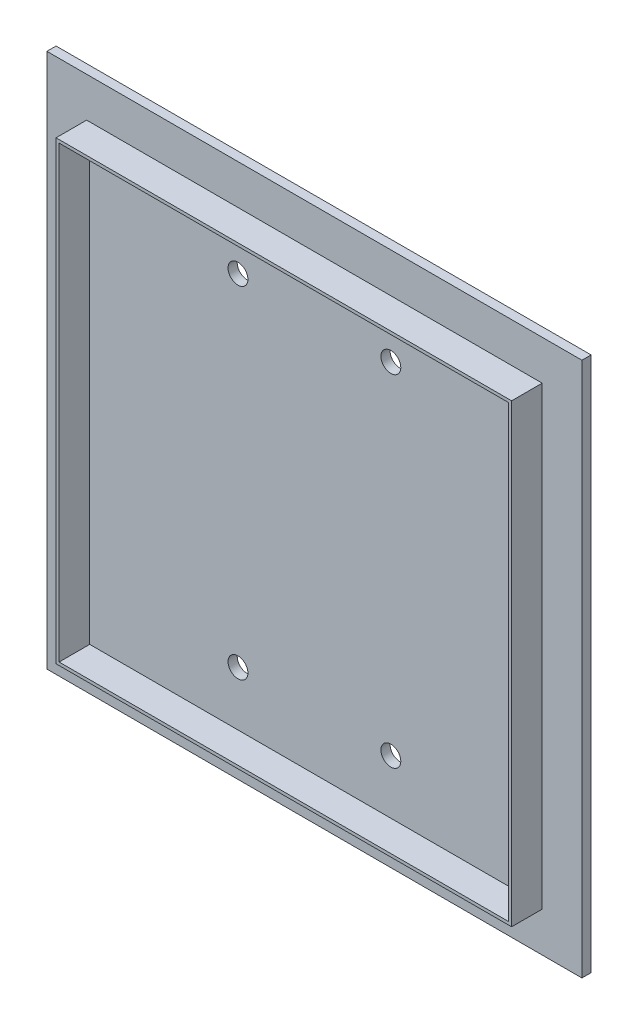
SolidWorks part; units mm, degrees
ref_plane "Plan de face" through (0, 0, 0) normal (0, 0, 1) x (1, 0, 0)
ref_plane "Plan de dessus" through (0, 0, 0) normal (0, 1, 0) x (1, 0, 0)
ref_plane "Plan de droite" through (0, 0, 0) normal (1, 0, 0) x (0, 0, -1)
sketch "Esquisse1" plane through (0, 0, 0) normal (0, 0, 1) x (1, 0, 0)
  line L1 (-175, -175) -> (175, -175)
  line L2 (-175, -175) -> (-175, 175)
  line L3 (-175, 175) -> (175, 175)
  line L4 (175, -175) -> (175, 175)
  line L5 (-175, -175) -> (175, 175) construction
  line L6 (-175, 175) -> (175, -175) construction
  point P0 (0, 0)
  dimension "D1" = 350
  dimension "D2" = 350
extrude "Boss.-Extru.1" add sketch "Esquisse1" along normal blind 26
sketch "Esquisse2" plane through (0, 0, 26) normal (0, 0, 1) x (1, 0, 0)
  line L1 (-149, 149) -> (149, 149)
  line L2 (-149, 149) -> (-149, -149)
  line L3 (-149, -149) -> (149, -149)
  line L4 (149, 149) -> (149, -149)
  line L5 (-149, 149) -> (149, -149) construction
  line L6 (-149, -149) -> (149, 149) construction
  line L7 (-175, 175) -> (175, 175)
  line L8 (-175, 175) -> (-175, -175)
  line L9 (-175, -175) -> (175, -175)
  line L10 (175, 175) -> (175, -175)
  line L11 (-175, 175) -> (175, -175) construction
  line L12 (-175, -175) -> (175, 175) construction
  point P0 (0, 0)
  point P6 (0, 0)
  dimension "D1" = 298
  dimension "D2" = 298
  dimension "D3" = 350
  dimension "350" = 350
extrude "Enlèv. mat.-Extru.1" cut sketch "Esquisse2" against normal blind 20
sketch "Esquisse3" plane through (0, 0, 26) normal (0, 0, 1) x (1, 0, 0)
  line L1 (-147, 147) -> (147, 147)
  line L2 (-147, 147) -> (-147, -147)
  line L3 (-147, -147) -> (147, -147)
  line L4 (147, 147) -> (147, -147)
  line L5 (-147, 147) -> (147, -147) construction
  line L6 (-147, -147) -> (147, 147) construction
  point P0 (0, 0)
  dimension "D1" = 294
  dimension "D2" = 294
extrude "Enlèv. mat.-Extru.2" cut sketch "Esquisse3" against normal blind 20
sketch "Esquisse5" plane through (0, 0, 0) normal (0, 0, -1) x (-1, 0, 0)
  line L0 (0, -199.0018) -> (0, 238.4235) construction
  line L1 (-175, 175) -> (175, 175)
  line L2 (-331.8191, 111.5) -> (288.8265, 111.5)
  line L3 (-270.0998, 0) -> (248.7223, 0) construction
  circle A0 centre (-50, 111.5) radius 6.5
  circle A1 centre (50, 111.5) radius 6.5
  circle A2 centre (50, -111.5) radius 6.5
  circle A3 centre (-50, -111.5) radius 6.5
  dimension "D2" = 13
  dimension "D1" = 63.5
  dimension "D3" = 50
extrude "Enlèv. mat.-Extru.3" cut sketch "Esquisse5" against normal through all both and the other way through all contours A0 | A1 | A2 | A3
